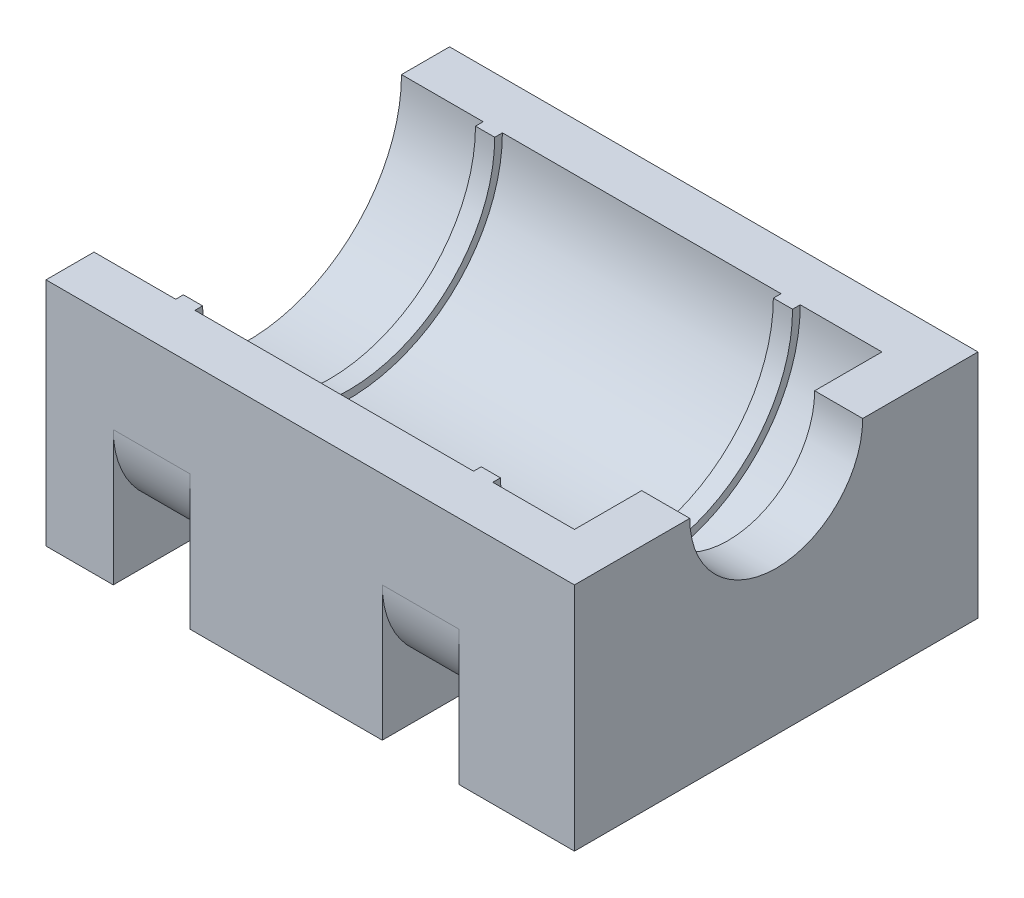
SolidWorks part; units mm, degrees
ref_plane "Front Plane" through (0, 0, 0) normal (0, 0, 1) x (1, 0, 0)
ref_plane "Top Plane" through (0, 0, 0) normal (0, 1, 0) x (1, 0, 0)
ref_plane "Right Plane" through (0, 0, 0) normal (1, 0, 0) x (0, 0, -1)
sketch "Sketch1" plane through (0, 0, 0) normal (0, 1, 0) x (1, 0, 0)
  line L1 (-13.75, -10.5) -> (13.75, -10.5)
  line L2 (-13.75, -10.5) -> (-13.75, 10.5)
  line L3 (-13.75, 10.5) -> (13.75, 10.5)
  line L4 (13.75, -10.5) -> (13.75, 10.5)
  line L5 (-13.75, -10.5) -> (13.75, 10.5) construction
  line L6 (-13.75, 10.5) -> (13.75, -10.5) construction
  point P0 (0, 0)
  dimension "D1" = 27.5
  dimension "D2" = 21
extrude "Boss-Extrude1" add sketch "Sketch1" along normal blind 12
sketch "Sketch2" plane through (0, 12, 0) normal (0, 1, 0) x (1, 0, 0)
  line L0 (-13.75, 0) -> (18.9071, 0) construction
  line L1 (-13.75, 10.5) -> (-13.75, -10.5) construction
  line L2 (-13.75, 0) -> (13.75, 0)
  line L3 (13.75, -10.5) -> (13.75, 10.5) construction
  line L4 (13.75, 0) -> (13.75, 4.5)
  line L5 (13.75, 4.5) -> (11.25, 4.5)
  line L6 (11.25, 4.5) -> (11.25, 8)
  line L7 (11.25, 8) -> (7, 8)
  line L8 (7, 8) -> (7, 7.6)
  line L9 (7, 7.6) -> (6, 7.6)
  line L10 (6, 7.6) -> (6, 8)
  line L11 (6, 8) -> (-8.5, 8)
  line L12 (-8.5, 8) -> (-8.5, 7.6)
  line L13 (-8.5, 7.6) -> (-9.5, 7.6)
  line L14 (-9.5, 7.6) -> (-9.5, 8)
  line L15 (-9.5, 8) -> (-13.75, 8)
  line L16 (-13.75, 8) -> (-13.75, 0)
  dimension "D1" = 2.5
  dimension "D2" = 16
  dimension "D3" = 1
  dimension "D4" = 0.4
  dimension "D5" = 16.5
  dimension "D6" = 9
revolve "Cut-Revolve1" cut sketch "Sketch2" angle 360 about L0
sketch "Sketch4" plane through (0, 0, 10.5) normal (0, 0, 1) x (1, 0, 0)
  line L0 (-13.75, 0) -> (13.75, 0) construction
  line L1 (-10.25, 0) -> (-6.25, 0)
  line L2 (-10.25, 0) -> (-10.25, 2)
  line L3 (-10.25, 2) -> (-6.25, 2)
  line L4 (-6.25, 0) -> (-6.25, 2)
  line L5 (11.25, 0) -> (11.25, 7.3043) construction
  line L6 (3.75, 0) -> (7.75, 0)
  line L7 (3.75, 0) -> (3.75, 2)
  line L8 (3.75, 2) -> (7.75, 2)
  line L9 (7.75, 0) -> (7.75, 2)
  line L10 (11.25, 7.3043) -> (-13.75, 7.3043) construction
  line L11 (-13.75, 12) -> (-13.75, 0) construction
  line L12 (-6.25, 2) -> (3.75, 2) construction
  line L13 (-1.25, 2) -> (-1.25, 7.3043) construction
  line L14 (13.75, 12) -> (13.75, 0) construction
  dimension "D1" = 2.5
  dimension "D2" = 2
  dimension "D3" = 4
  dimension "D4" = 18
extrude "Cut-Extrude1" cut sketch "Sketch4" against normal through all
fillet "Fillet1" radius 5 4 edges at (-8.25, 2, 10.5) (5.75, 2, 10.5) (-8.25, 2, -10.5) (5.75, 2, -10.5)
